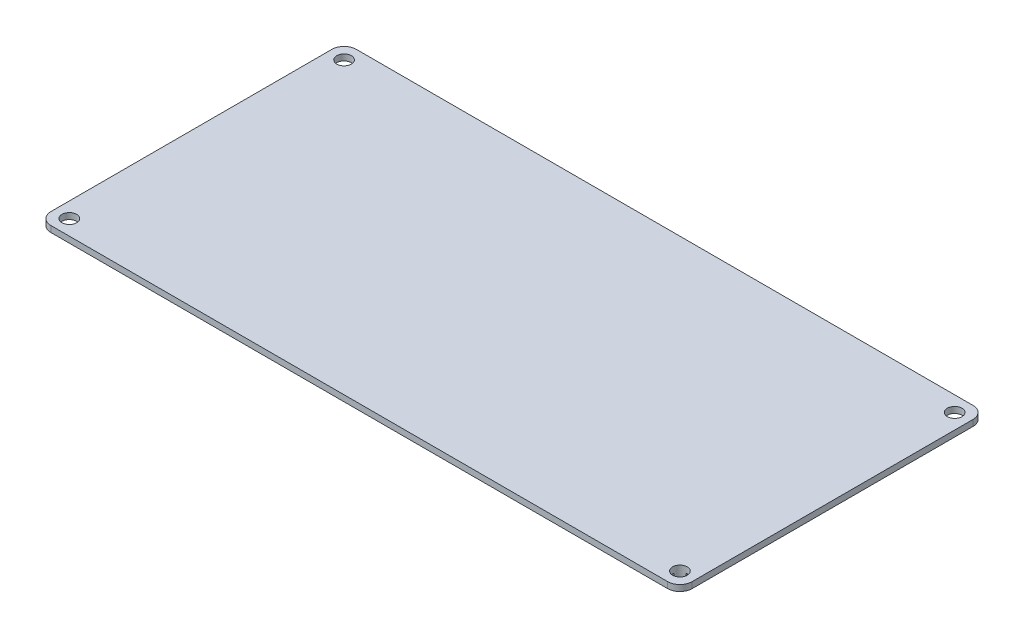
SolidWorks part; units mm, degrees
ref_plane "Front Plane" through (0, 0, 0) normal (0, 0, 1) x (1, 0, 0)
ref_plane "Top Plane" through (0, 0, 0) normal (0, 1, 0) x (1, 0, 0)
ref_plane "Right Plane" through (0, 0, 0) normal (1, 0, 0) x (0, 0, -1)
sketch "Sketch2" plane through (0, 0, 0) normal (0, 1, 0) x (1, 0, 0)
  line L1 (-63.5, 28.575) -> (63.5, 28.575)
  line L2 (-63.5, 28.575) -> (-63.5, -28.575)
  line L3 (-63.5, -28.575) -> (63.5, -28.575)
  line L4 (63.5, 28.575) -> (63.5, -28.575)
  line L5 (-63.5, 28.575) -> (63.5, -28.575) construction
  line L6 (-63.5, -28.575) -> (63.5, 28.575) construction
  point P0 (0, 0)
  dimension "D1" = 57.15
  dimension "D2" = 127
extrude "Boss-Extrude3" add sketch "Sketch2" along normal blind 1.27
sketch "Sketch3" plane through (0, 1.27, 0) normal (0, 1, 0) x (1, 0, 0)
  line L0 (63.5, 28.575) -> (-63.5, 28.575) construction
  line L1 (-66.675, 31.75) -> (66.675, 31.75)
  line L2 (-66.675, 31.75) -> (-66.675, -31.75)
  line L3 (-66.675, -31.75) -> (66.675, -31.75)
  line L4 (66.675, 31.75) -> (66.675, -31.75)
  line L5 (-66.675, 31.75) -> (66.675, -31.75) construction
  line L6 (-66.675, -31.75) -> (66.675, 31.75) construction
  line L7 (63.5, -28.575) -> (63.5, 28.575) construction
  point P0 (0, 0)
  dimension "D1" = 3.175
  dimension "D2" = 3.175
extrude "Boss-Extrude4" add sketch "Sketch3" along normal blind 1.27
sketch "Sketch4" plane through (0, 0, 0) normal (0, -1, 0) x (-1, 0, 0)
  circle A0 centre (63.5, -28.575) radius 1.524
  circle A1 centre (-63.5, -28.575) radius 1.524
  circle A2 centre (-63.5, 28.575) radius 1.524
  circle A3 centre (63.5, 28.575) radius 1.524
  dimension "D1" = 3.048
extrude "Cut-Extrude1" cut sketch "Sketch4" against normal through all
fillet "Fillet1" radius 2.54 4 edges at (-66.675, 1.905, 31.75) (-66.675, 1.905, -31.75) (66.675, 1.905, -31.75) (66.675, 1.905, 31.75)
sketch "Sketch5" plane through (0, 0, 0) normal (0, -1, 0) x (-1, 0, 0)
  line L0 (-63.5, -27.051) -> (-63.5, 27.051) construction
  line L1 (63.2714, -28.3464) -> (-63.2714, -28.3464)
  line L2 (63.2714, -28.3464) -> (63.2714, 28.3464)
  line L3 (63.2714, 28.3464) -> (-63.2714, 28.3464)
  line L4 (-63.2714, -28.3464) -> (-63.2714, 28.3464)
  line L5 (63.2714, -28.3464) -> (-63.2714, 28.3464) construction
  line L6 (63.2714, 28.3464) -> (-63.2714, -28.3464) construction
  line L7 (-61.976, 28.575) -> (61.976, 28.575) construction
  line L8 (-61.976, 28.575) -> (61.976, 28.575) construction
  line L9 (63.5, -28.575) -> (-63.5, -28.575)
  line L10 (63.5, -28.575) -> (63.5, 28.575)
  line L11 (63.5, 28.575) -> (-63.5, 28.575)
  line L12 (-63.5, -28.575) -> (-63.5, 28.575)
  line L13 (63.5, -28.575) -> (-63.5, 28.575) construction
  line L14 (63.5, 28.575) -> (-63.5, -28.575) construction
  line L15 (-63.5, -27.051) -> (-63.5, 27.051) construction
  point P0 (0, 0)
  point P10 (0, 0)
  point P15 (-64.1129, 29.1022)
  dimension "D1" = 0.2286
  dimension "D2" = 0.2286
extrude "Cut-Extrude2" cut sketch "Sketch5" against normal up to surface (1.27 mm away) up to face at (0, 1.27, 0)
